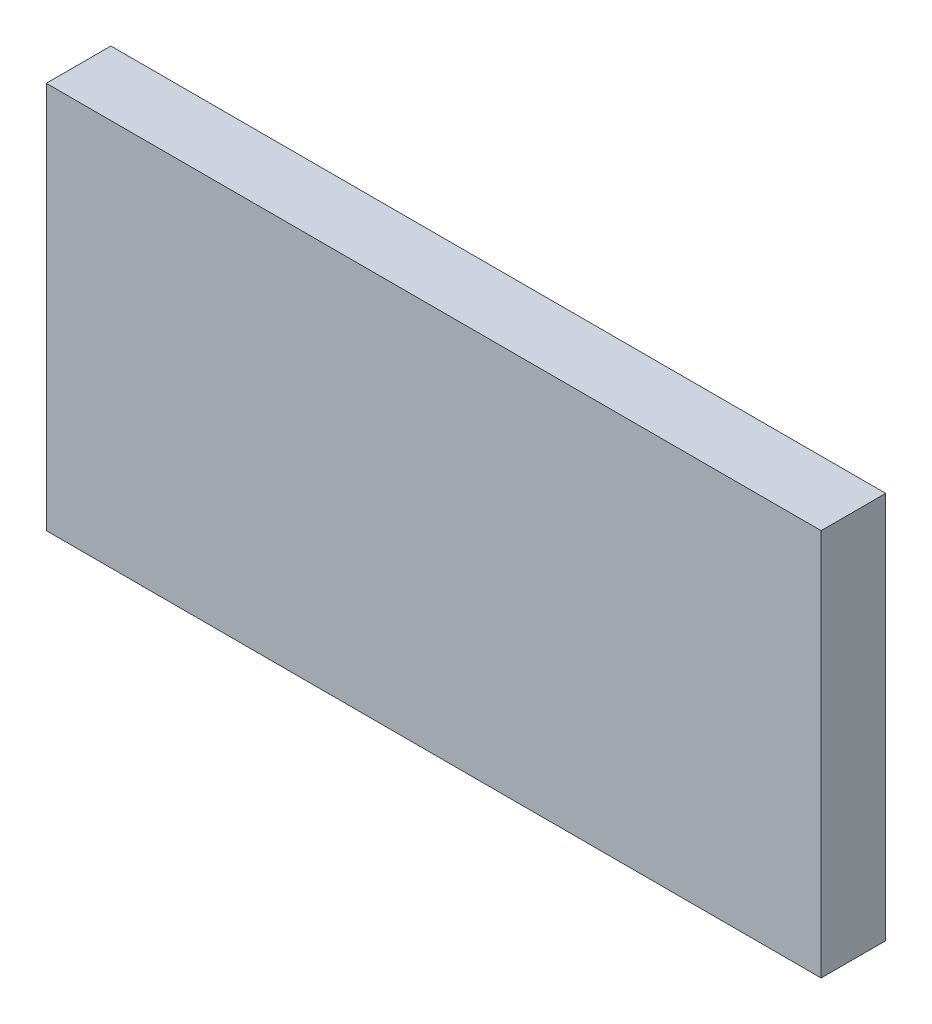
SolidWorks part; units mm, degrees
ref_plane "Front Plane" through (0, 0, 0) normal (0, 0, 1) x (1, 0, 0)
ref_plane "Top Plane" through (0, 0, 0) normal (0, 1, 0) x (1, 0, 0)
ref_plane "Right Plane" through (0, 0, 0) normal (1, 0, 0) x (0, 0, -1)
sketch "Sketch1" plane through (0, 0, 0) normal (0, 0, 1) x (1, 0, 0)
  line L1 (-38.1, -19.05) -> (38.1, -19.05)
  line L2 (-38.1, -19.05) -> (-38.1, 19.05)
  line L3 (-38.1, 19.05) -> (38.1, 19.05)
  line L4 (38.1, -19.05) -> (38.1, 19.05)
  line L5 (-38.1, -19.05) -> (38.1, 19.05) construction
  line L6 (-38.1, 19.05) -> (38.1, -19.05) construction
  point P0 (0, 0)
  dimension "D1" = 76.2
  dimension "D2" = 38.1
extrude "Boss-Extrude1" add sketch "Sketch1" along normal blind 6.35
